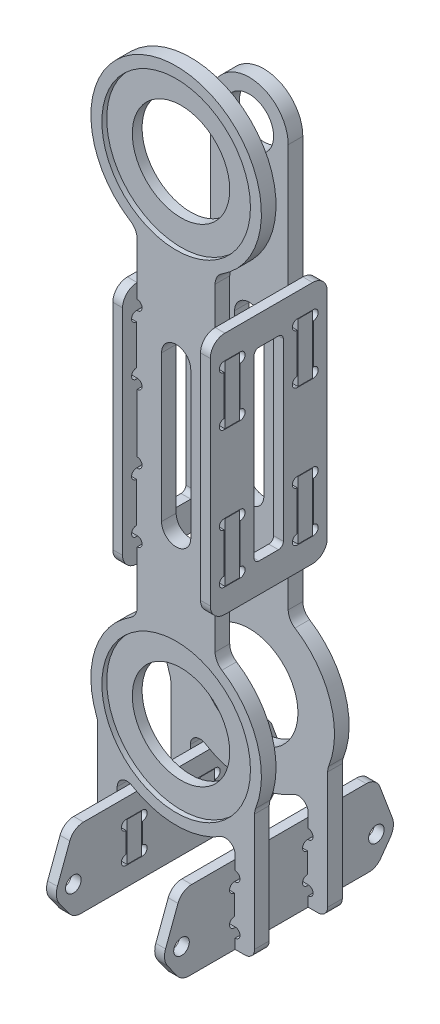
SolidWorks part; units mm, degrees
material "碳板"
ref_plane "前视基准面" through (0, 0, 0) normal (0, 0, 1) x (1, 0, 0)
ref_plane "上视基准面" through (0, 0, 0) normal (0, 1, 0) x (1, 0, 0)
ref_plane "右视基准面" through (0, 0, 0) normal (1, 0, 0) x (0, 0, -1)
sketch "草图1" plane through (0, 0, 0) normal (0, 0, 1) x (1, 0, 0)
  line L0 (0, 44.0591) -> (0, -33.3928) construction
  line L1 (-50.3013, 0) -> (44.4833, 0) construction
  circle A0 centre (0, 0) radius 10
  circle A1 centre (0, 0) radius 17.5
  circle A2 centre (0, 100) radius 10
  circle A3 centre (0, 100) radius 17.5
  point P11 (0, 0)
  dimension "D1" = 20
  dimension "D2" = 35
  dimension "D3" = 100
sketch "草图2" plane through (0, 0, 0) normal (1, 0, 0) x (0, 0, -1)
  line L0 (20, -33.5) -> (-20, -33.5)
  line L1 (0, 200044.0591) -> (0, -200033.3928) construction
  line L2 (-85.8651, -27.5) -> (83.6883, -27.5) construction
  line L7 (20, -17.5) -> (-20, -17.5)
  line L8 (0, 0) -> (0, -50.5877) construction
  line L9 (5.85, -21.4) -> (9.15, -21.4)
  line L10 (5.85, -23.4) -> (5.85, -27.6)
  line L11 (5.85, -29.6) -> (9.15, -29.6)
  line L12 (9.15, -23.4) -> (9.15, -27.6)
  line L13 (5.85, -21.4) -> (9.15, -29.6) construction
  line L14 (5.85, -29.6) -> (9.15, -21.4) construction
  line L15 (-20, -17.5) -> (-23.2786, -26.275)
  line L16 (-20, -33.5) -> (-22.8428, -29.5417)
  line L17 (20, -33.5) -> (22.8428, -29.5417)
  line L18 (20, -17.5) -> (23.2786, -26.275)
  line L19 (-5.85, -21.4) -> (-9.15, -21.4)
  line L20 (-5.85, -23.4) -> (-5.85, -27.6)
  line L21 (-5.85, -29.6) -> (-9.15, -29.6)
  line L22 (-9.15, -23.4) -> (-9.15, -27.6)
  line L23 (-7.5, -21.4) -> (-7.5, -29.6) construction
  circle A0 centre (-20, -27.5) radius 1.6
  circle A1 centre (20, -27.5) radius 1.6
  arc A4 (-23.2786, -26.275) -> (-22.8428, -29.5417) centre (-20, -27.5) ccw
  arc A5 (23.2786, -26.275) -> (22.8428, -29.5417) centre (20, -27.5) cw
  arc A6 (5.85, -21.4) -> (5.85, -23.4) centre (5.85, -22.4) ccw
  arc A7 (9.15, -23.4) -> (9.15, -21.4) centre (9.15, -22.4) ccw
  arc A8 (5.85, -27.6) -> (5.85, -29.6) centre (5.85, -28.6) ccw
  arc A9 (9.15, -29.6) -> (9.15, -27.6) centre (9.15, -28.6) ccw
  arc A10 (-9.15, -23.4) -> (-9.15, -21.4) centre (-9.15, -22.4) cw
  arc A11 (-5.85, -21.4) -> (-5.85, -23.4) centre (-5.85, -22.4) cw
  arc A12 (-5.85, -27.6) -> (-5.85, -29.6) centre (-5.85, -28.6) cw
  arc A13 (-9.15, -29.6) -> (-9.15, -27.6) centre (-9.15, -28.6) cw
  point P3 (7.5, -25.5)
  point P21 (0, -33.5)
  point P27 (0, -17.5)
  dimension "D1" = 3.2
  dimension "D4" = 6
  dimension "D6" = 7
  dimension "D10" = 2
  dimension "D2" = 40
  dimension "D3" = 27.5
  dimension "D5" = 10
  dimension "D7" = 3.3
  dimension "D8" = 8
  dimension "D9" = 8.2
  dimension "D11" = 15
extrude "凸台-拉伸1" add sketch "草图2" along normal blind 2 from offset 10.1
fillet "圆角1" radius 3 4 edges at (11.1, -33.5, -20) (11.1, -17.5, 20) (11.1, -17.5, -20) (11.1, -33.5, 20)
mirror "镜向2" about plane through (0, 0, 0) normal (1, 0, 0) of bodies 106
ref_plane "基准面1" through (0, 0, 7.5) normal (0, 0, -1) x (-1, 0, 0)
sketch "草图3" plane through (0, 0, 7.5) normal (0, 0, -1) x (-1, 0, 0)
  line L0 (-12.1, -23.4) -> (-10.1, -23.4) construction
  line L1 (-12.1, -23.4) -> (-10.1, -23.4) construction
  line L2 (-12.1, -27.6) -> (-10.1, -27.6) construction
  line L3 (-12.1, -27.6) -> (-10.1, -27.6) construction
  line L4 (-11.1, -23.4) -> (-11.1, -27.6) construction
  line L5 (-11.1, -25.5) -> (-7.6378, -25.5) construction
  line L6 (-12.1, -21.5) -> (-10.1, -21.5)
  line L7 (-10.1, -21.5) -> (-10.1, -29.5)
  line L8 (-12.1, -19.5) -> (-12.1, -12.6428)
  line L9 (-12.1, -29.5) -> (-10.1, -29.5)
  line L10 (-12.1, -31.5) -> (-12.1, -33.5)
  line L11 (0, 35) -> (0, 65) construction
  line L12 (-12.1, -33.5) -> (-16.1, -33.5)
  line L13 (-3, 35) -> (-3, 65)
  line L14 (-16.1, -33.5) -> (-16.1, -6.8586)
  line L15 (-8, 84.4356) -> (-8, 72)
  line L16 (3, 35) -> (3, 65)
  line L17 (0, 144.5761) -> (0, -67.6528) construction
  line L18 (8, 84.4356) -> (8, 72)
  line L19 (12.1, -21.5) -> (10.1, -21.5)
  line L20 (10.1, -21.5) -> (10.1, -29.5)
  line L21 (12.1, -29.5) -> (10.1, -29.5)
  line L22 (12.1, -31.5) -> (12.1, -33.5)
  line L23 (12.1, -33.5) -> (16.1, -33.5)
  line L24 (16.1, -33.5) -> (16.1, -6.8586)
  line L25 (12.1, -19.5) -> (12.1, -12.6428)
  line L26 (8, 50) -> (-8, 50) construction
  line L27 (8, 70) -> (10, 70)
  line L28 (10, 70) -> (10, 58)
  line L29 (10, 58) -> (8, 58)
  line L30 (10, 42) -> (8, 42)
  line L31 (10, 30) -> (10, 42)
  line L32 (8, 30) -> (10, 30)
  line L33 (-10, 70) -> (-10, 58)
  line L34 (-8, 70) -> (-10, 70)
  line L35 (-10, 58) -> (-8, 58)
  line L36 (-8, 30) -> (-10, 30)
  line L37 (-10, 30) -> (-10, 42)
  line L38 (-10, 42) -> (-8, 42)
  line L39 (8, 28) -> (8, 15.5644)
  line L41 (-8, 28) -> (-8, 15.5644)
  line L43 (-8, 56) -> (-8, 44)
  line L46 (8, 56) -> (8, 44)
  circle A0 centre (0, 0) radius 10 construction
  circle A1 centre (0, 0) radius 10
  circle A2 centre (0, 0) radius 17.5 construction
  arc A3 (-12.1, -12.6428) -> (12.1, -12.6428) centre (0, 0) ccw
  circle A4 centre (0, 100) radius 10 construction
  circle A5 centre (0, 100) radius 10
  circle A6 centre (0, 100) radius 17.5 construction
  arc A7 (8, 84.4356) -> (-8, 84.4356) centre (0, 100) ccw
  arc A8 (-12.1, -19.5) -> (-12.1, -21.5) centre (-12.1, -20.5) ccw
  arc A9 (-12.1, -31.5) -> (-12.1, -29.5) centre (-12.1, -30.5) cw
  arc A10 (-8, 15.5644) -> (-16.1, -6.8586) centre (0, 0) ccw
  arc A11 (12.1, -19.5) -> (12.1, -21.5) centre (12.1, -20.5) cw
  arc A12 (12.1, -31.5) -> (12.1, -29.5) centre (12.1, -30.5) ccw
  arc A13 (16.1, -6.8586) -> (8, 15.5644) centre (0, 0) ccw
  arc A14 (-3, 35) -> (3, 35) centre (0, 35) ccw
  arc A15 (3, 65) -> (-3, 65) centre (0, 65) ccw
  arc A16 (8, 72) -> (8, 70) centre (8, 71) ccw
  arc A17 (8, 58) -> (8, 56) centre (8, 57) ccw
  arc A18 (8, 42) -> (8, 44) centre (8, 43) cw
  arc A19 (8, 28) -> (8, 30) centre (8, 29) cw
  arc A20 (-8, 58) -> (-8, 56) centre (-8, 57) cw
  arc A21 (-8, 72) -> (-8, 70) centre (-8, 71) cw
  arc A22 (-8, 28) -> (-8, 30) centre (-8, 29) ccw
  arc A23 (-8, 42) -> (-8, 44) centre (-8, 43) ccw
  point P29 (-10.1, -25.5)
  point P52 (0, 50)
  point P89 (0, 0)
  point P90 (0, 0)
  point P91 (0, 0)
  point P92 (0, 0)
  point P93 (0, 0)
  point P94 (0, 0)
  point P95 (0, 0)
  point P96 (0, 0)
  point P97 (0, 0)
  point P98 (0, 0)
  point P99 (0, 0)
  point P100 (0, 63.2924)
  dimension "D1" = 2
  dimension "D9" = 2
  dimension "D2" = 2
  dimension "D3" = 8
  dimension "D4" = 2
  dimension "D5" = 4
  dimension "D6" = 16
  dimension "D7" = 6
  dimension "D8" = 30
  dimension "D10" = 2
  dimension "D11" = 12
  dimension "D12" = 12
  dimension "D13" = 50
extrude "凸台-拉伸2" add sketch "草图3" along normal mid plane 3 separate body
fillet "圆角2" radius 2 4 edges at (16.1, -33.5, 7.5) (12.1, -12.6428, 7.5) (-12.1, -12.6428, 7.5) (-16.1, -33.5, 7.5)
fillet "圆角3" radius 3 6 edges at (-8, 84.4356, 7.5) (8, 84.4356, 7.5) (8, 15.5644, 7.5) (-8, 15.5644, 7.5) (16.1, -6.8586, 7.5) (-16.1, -6.8586, 7.5)
ref_plane "基准面2" through (0, 0, -7.5) normal (0, 0, 1) x (1, 0, 0)
sketch "草图4" plane through (0, 0, -7.5) normal (0, 0, 1) x (1, 0, 0)
  line L0 (0, 133.8985) -> (0, -64.2297) construction
  line L1 (-69.7714, 0) -> (67.8542, 0) construction
  line L2 (-8, 72) -> (-8, 82.7012) construction
  line L3 (-8, 72) -> (-8, 100)
  line L4 (8, 82.7012) -> (8, 72) construction
  line L5 (8, 100) -> (8, 72)
  line L6 (-10, 70) -> (-8, 70) construction
  line L7 (-10, 70) -> (-8, 70)
  line L8 (-10, 58) -> (-10, 70) construction
  line L9 (-10, 58) -> (-10, 70)
  line L10 (-8, 58) -> (-10, 58) construction
  line L11 (-8, 58) -> (-10, 58)
  line L12 (-8, 44) -> (-8, 56) construction
  line L13 (-8, 44) -> (-8, 56)
  line L14 (-10, 42) -> (-8, 42) construction
  line L15 (-10, 42) -> (-8, 42)
  line L16 (-10, 30) -> (-10, 42) construction
  line L17 (-10, 30) -> (-10, 42)
  line L18 (-8, 30) -> (-10, 30) construction
  line L19 (-8, 30) -> (-10, 30)
  line L20 (-12.1, -21.5) -> (-10.1, -21.5) construction
  line L21 (-12.1, -21.5) -> (-10.1, -21.5)
  line L22 (-10.1, -21.5) -> (-10.1, -29.5) construction
  line L23 (-10.1, -21.5) -> (-10.1, -29.5)
  line L24 (-10.1, -29.5) -> (-12.1, -29.5) construction
  line L25 (-10.1, -29.5) -> (-12.1, -29.5)
  line L26 (-12.1, -31.5) -> (-12.1, -33.5) construction
  line L27 (-12.1, -31.5) -> (-12.1, -33.5)
  line L28 (-12.1, -33.5) -> (-14.1, -33.5) construction
  line L29 (-12.1, -33.5) -> (-14.1, -33.5)
  line L30 (-16.1, -31.5) -> (-16.1, -7.4458) construction
  line L31 (-16.1, -31.5) -> (-16.1, -7.4458)
  line L32 (-12.1, -16.6805) -> (-12.1, -19.5) construction
  line L33 (-12.1, -16.6805) -> (-12.1, -19.5)
  line L35 (-8, 17.2988) -> (-8, 28) construction
  line L36 (8, 70) -> (10, 70) construction
  line L37 (8, 70) -> (10, 70)
  line L38 (10, 70) -> (10, 58) construction
  line L39 (10, 70) -> (10, 58)
  line L40 (10, 58) -> (8, 58) construction
  line L41 (10, 58) -> (8, 58)
  line L42 (8, 56) -> (8, 44) construction
  line L43 (8, 56) -> (8, 44)
  line L44 (8, 42) -> (10, 42) construction
  line L45 (8, 42) -> (10, 42)
  line L46 (10, 42) -> (10, 30) construction
  line L47 (10, 42) -> (10, 30)
  line L48 (10, 30) -> (8, 30) construction
  line L49 (10, 30) -> (8, 30)
  line L50 (8, 28) -> (8, 17.2988) construction
  line L51 (8, 28) -> (8, 17.2988)
  line L52 (-8, 17.2988) -> (-8, 28)
  line L53 (16.1, -7.4458) -> (16.1, -31.5) construction
  line L54 (16.1, -7.4458) -> (16.1, -31.5)
  line L55 (14.1, -33.5) -> (12.1, -33.5) construction
  line L56 (14.1, -33.5) -> (12.1, -33.5)
  line L57 (12.1, -33.5) -> (12.1, -31.5) construction
  line L58 (12.1, -33.5) -> (12.1, -31.5)
  line L59 (12.1, -29.5) -> (10.1, -29.5) construction
  line L60 (12.1, -29.5) -> (10.1, -29.5)
  line L61 (10.1, -29.5) -> (10.1, -21.5) construction
  line L62 (10.1, -29.5) -> (10.1, -21.5)
  line L63 (10.1, -21.5) -> (12.1, -21.5) construction
  line L64 (10.1, -21.5) -> (12.1, -21.5)
  line L65 (12.1, -19.5) -> (12.1, -16.6805) construction
  line L66 (12.1, -19.5) -> (12.1, -16.6805)
  line L67 (-3, 35) -> (-3, 65) construction
  line L68 (-3, 35) -> (-3, 65)
  line L69 (3, 65) -> (3, 35) construction
  line L70 (3, 65) -> (3, 35)
  circle A0 centre (0, 0) radius 10 construction
  circle A1 centre (0, 0) radius 10 construction
  circle A2 centre (0, 100) radius 10 construction
  circle A3 centre (0, 100) radius 10 construction
  arc A4 (8, 100) -> (-8, 100) centre (0, 100) ccw
  circle A5 centre (0, 100) radius 5
  arc A8 (-8, 70) -> (-8, 72) centre (-8, 71) ccw construction
  arc A9 (-8, 70) -> (-8, 72) centre (-8, 71) ccw
  arc A10 (8, 72) -> (8, 70) centre (8, 71) ccw construction
  arc A11 (8, 72) -> (8, 70) centre (8, 71) ccw
  arc A12 (-8, 56) -> (-8, 58) centre (-8, 57) ccw construction
  arc A13 (-8, 56) -> (-8, 58) centre (-8, 57) ccw
  arc A14 (-8, 42) -> (-8, 44) centre (-8, 43) ccw construction
  arc A15 (-8, 42) -> (-8, 44) centre (-8, 43) ccw
  arc A16 (-8, 28) -> (-8, 30) centre (-8, 29) ccw construction
  arc A17 (-8, 28) -> (-8, 30) centre (-8, 29) ccw
  arc A18 (-12.1, -29.5) -> (-12.1, -31.5) centre (-12.1, -30.5) ccw construction
  arc A19 (-12.1, -29.5) -> (-12.1, -31.5) centre (-12.1, -30.5) ccw
  arc A20 (-16.1, -31.5) -> (-14.1, -33.5) centre (-14.1, -31.5) ccw construction
  arc A21 (-16.1, -31.5) -> (-14.1, -33.5) centre (-14.1, -31.5) ccw
  arc A22 (-12.1, -19.5) -> (-12.1, -21.5) centre (-12.1, -20.5) ccw construction
  arc A23 (-12.1, -19.5) -> (-12.1, -21.5) centre (-12.1, -20.5) ccw
  arc A25 (8, 58) -> (8, 56) centre (8, 57) ccw construction
  arc A26 (8, 58) -> (8, 56) centre (8, 57) ccw
  arc A27 (8, 44) -> (8, 42) centre (8, 43) ccw construction
  arc A28 (8, 44) -> (8, 42) centre (8, 43) ccw
  arc A29 (8, 30) -> (8, 28) centre (8, 29) ccw construction
  arc A30 (8, 30) -> (8, 28) centre (8, 29) ccw
  arc A31 (-9.3902, 14.7673) -> (-8, 17.2988) centre (-11, 17.2988) ccw construction
  arc A32 (-9.3902, 14.7673) -> (-8, 17.2988) centre (-11, 17.2988) ccw
  arc A33 (-9.3902, 14.7673) -> (-16.3049, -6.3562) centre (0, 0) ccw construction
  arc A34 (-9.3902, 14.7673) -> (-16.3049, -6.3562) centre (0, 0) ccw
  arc A35 (8, 17.2988) -> (9.3902, 14.7673) centre (11, 17.2988) ccw construction
  arc A36 (8, 17.2988) -> (9.3902, 14.7673) centre (11, 17.2988) ccw
  arc A37 (16.3049, -6.3562) -> (9.3902, 14.7673) centre (0, 0) ccw construction
  arc A38 (16.3049, -6.3562) -> (9.3902, 14.7673) centre (0, 0) ccw
  arc A39 (-16.1, -7.4458) -> (-16.3049, -6.3562) centre (-19.1, -7.4458) ccw construction
  arc A40 (-16.1, -7.4458) -> (-16.3049, -6.3562) centre (-19.1, -7.4458) ccw
  arc A41 (16.3049, -6.3562) -> (16.1, -7.4458) centre (19.1, -7.4458) ccw construction
  arc A42 (16.3049, -6.3562) -> (16.1, -7.4458) centre (19.1, -7.4458) ccw
  arc A43 (14.1, -33.5) -> (16.1, -31.5) centre (14.1, -31.5) ccw construction
  arc A44 (14.1, -33.5) -> (16.1, -31.5) centre (14.1, -31.5) ccw
  arc A45 (12.1, -31.5) -> (12.1, -29.5) centre (12.1, -30.5) ccw construction
  arc A46 (12.1, -31.5) -> (12.1, -29.5) centre (12.1, -30.5) ccw
  arc A47 (12.1, -21.5) -> (12.1, -19.5) centre (12.1, -20.5) ccw construction
  arc A48 (12.1, -21.5) -> (12.1, -19.5) centre (12.1, -20.5) ccw
  arc A49 (12.1, -16.6805) -> (9.0641, -14.9697) centre (10.1, -16.6805) ccw construction
  arc A50 (12.1, -16.6805) -> (9.0641, -14.9697) centre (10.1, -16.6805) ccw
  arc A51 (-9.0641, -14.9697) -> (9.0641, -14.9697) centre (0, 0) ccw construction
  arc A52 (-9.0641, -14.9697) -> (9.0641, -14.9697) centre (0, 0) ccw
  arc A53 (-9.0641, -14.9697) -> (-12.1, -16.6805) centre (-10.1, -16.6805) ccw construction
  arc A54 (-9.0641, -14.9697) -> (-12.1, -16.6805) centre (-10.1, -16.6805) ccw
  circle A55 centre (0, 0) radius 10
  arc A56 (3, 65) -> (-3, 65) centre (0, 65) ccw construction
  arc A57 (3, 65) -> (-3, 65) centre (0, 65) ccw
  arc A58 (-3, 35) -> (3, 35) centre (0, 35) ccw construction
  arc A59 (-3, 35) -> (3, 35) centre (0, 35) ccw
  dimension "D1" = 10
  dimension "D2" = 16
extrude "凸台-拉伸3" add sketch "草图4" along normal mid plane 3 separate body
sketch "草图5" plane through (0, 0, 9) normal (0, 0, 1) x (1, 0, 0)
  circle A0 centre (0, 100) radius 15.25
  circle A1 centre (0, 0) radius 15.25
  dimension "D1" = 30.5
extrude "切除-拉伸1" cut sketch "草图5" against normal blind 1
sketch "草图6" plane through (-10, 0, 0) normal (-1, 0, 0) x (0, 0, 1)
  line L0 (0, 115.7187) -> (0, -52.1823) construction
  line L1 (-9, 58) -> (-9, 42) construction
  line L2 (-9, 50) -> (17.8852, 50) construction
  line L3 (-7.5, 70) -> (-7.5, 58) construction
  line L4 (-12, 75) -> (12, 75)
  line L5 (-12, 75) -> (-12, 25)
  line L6 (-12, 25) -> (12, 25)
  line L7 (12, 75) -> (12, 25)
  line L8 (-12, 75) -> (12, 25) construction
  line L9 (-12, 25) -> (12, 75) construction
  line L10 (-3, 69) -> (3, 69)
  line L11 (-3, 69) -> (-3, 31)
  line L12 (-3, 31) -> (3, 31)
  line L13 (3, 69) -> (3, 31)
  line L14 (-3, 69) -> (3, 31) construction
  line L15 (-3, 31) -> (3, 69) construction
  line L16 (-6, 70) -> (-9, 70) construction
  line L17 (-6, 58) -> (-9, 58) construction
  line L18 (-9.15, 68.1) -> (-9.15, 59.9)
  line L19 (-9.15, 70.1) -> (-5.85, 70.1)
  line L21 (-9.15, 57.9) -> (-5.85, 57.9)
  line L22 (-5.85, 68.1) -> (-5.85, 59.9)
  line L23 (-9.15, 70.1) -> (-5.85, 57.9) construction
  line L24 (-9.15, 57.9) -> (-5.85, 70.1) construction
  line L25 (9.15, 70.1) -> (5.85, 70.1)
  line L26 (5.85, 68.1) -> (5.85, 59.9)
  line L27 (9.15, 57.9) -> (5.85, 57.9)
  line L28 (9.15, 68.1) -> (9.15, 59.9)
  line L29 (-9.15, 29.9) -> (-5.85, 29.9)
  line L30 (-5.85, 31.9) -> (-5.85, 40.1)
  line L31 (-9.15, 42.1) -> (-5.85, 42.1)
  line L32 (-9.15, 31.9) -> (-9.15, 40.1)
  line L33 (9.15, 29.9) -> (5.85, 29.9)
  line L34 (5.85, 31.9) -> (5.85, 40.1)
  line L35 (9.15, 42.1) -> (5.85, 42.1)
  line L36 (9.15, 31.9) -> (9.15, 40.1)
  arc A1 (-9.15, 59.9) -> (-9.15, 57.9) centre (-9.15, 58.9) ccw
  arc A2 (-5.85, 57.9) -> (-5.85, 59.9) centre (-5.85, 58.9) ccw
  arc A3 (-5.85, 68.1) -> (-5.85, 70.1) centre (-5.85, 69.1) ccw
  arc A4 (-9.15, 70.1) -> (-9.15, 68.1) centre (-9.15, 69.1) ccw
  arc A5 (9.15, 70.1) -> (9.15, 68.1) centre (9.15, 69.1) cw
  arc A6 (5.85, 68.1) -> (5.85, 70.1) centre (5.85, 69.1) cw
  arc A7 (5.85, 57.9) -> (5.85, 59.9) centre (5.85, 58.9) cw
  arc A8 (9.15, 59.9) -> (9.15, 57.9) centre (9.15, 58.9) cw
  arc A9 (-9.15, 29.9) -> (-9.15, 31.9) centre (-9.15, 30.9) cw
  arc A10 (-5.85, 31.9) -> (-5.85, 29.9) centre (-5.85, 30.9) cw
  arc A11 (-5.85, 42.1) -> (-5.85, 40.1) centre (-5.85, 41.1) cw
  arc A12 (-9.15, 40.1) -> (-9.15, 42.1) centre (-9.15, 41.1) cw
  arc A13 (5.85, 31.9) -> (5.85, 29.9) centre (5.85, 30.9) ccw
  arc A14 (5.85, 42.1) -> (5.85, 40.1) centre (5.85, 41.1) ccw
  arc A15 (9.15, 40.1) -> (9.15, 42.1) centre (9.15, 41.1) ccw
  arc A16 (9.15, 29.9) -> (9.15, 31.9) centre (9.15, 30.9) ccw
  point P9 (0, 50)
  point P14 (0, 50)
  point P26 (-7.5, 64)
  point P32 (-9.0926, 70)
  point P39 (-9.3016, 69.2787)
  point P42 (0, 0)
  point P43 (0, 0)
  point P44 (0, 0)
  point P45 (0, 0)
  dimension "D7" = 1
  dimension "D1" = 50
  dimension "D2" = 24
  dimension "D3" = 6
  dimension "D4" = 9
  dimension "D5" = 3.3
  dimension "D6" = 12.2
extrude "凸台-拉伸4" add sketch "草图6" against normal blind 2 separate body
fillet "圆角4" radius 3 4 edges at (-9, 75, -12) (-9, 25, -12) (-9, 25, 12) (-9, 75, 12)
fillet "圆角5" radius 1 4 edges at (-9, 31, -3) (-9, 69, 3) (-9, 31, 3) (-9, 69, -3)
mirror "镜向4" about plane through (0, 0, 0) normal (1, 0, 0) of bodies 112
